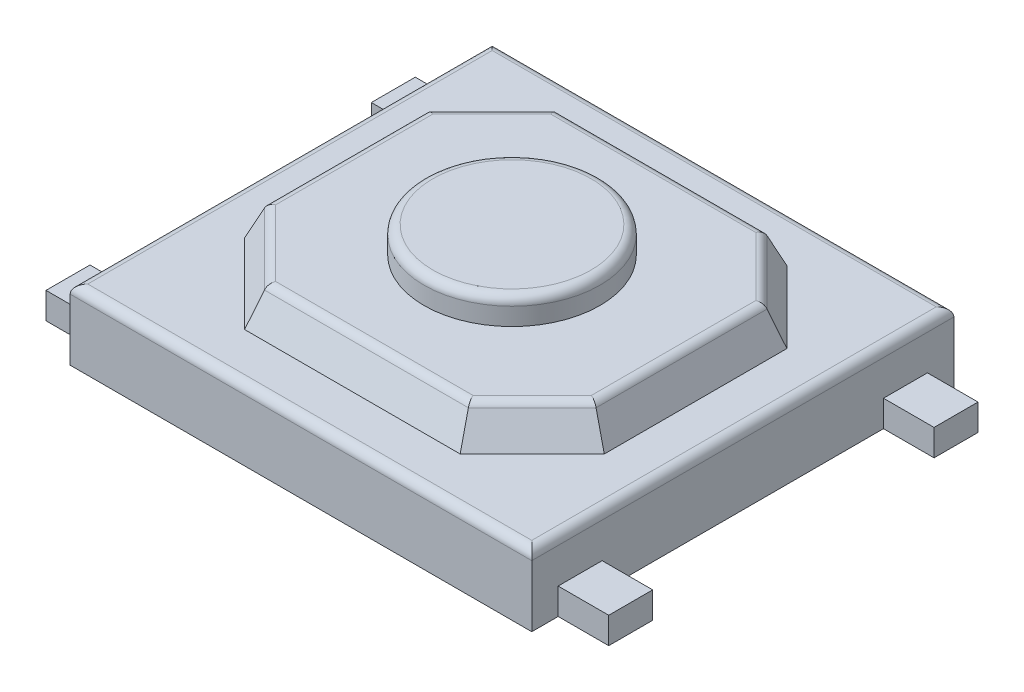
SolidWorks part; units mm, degrees
ref_plane "Front Plane" through (0, 0, 0) normal (0, 0, 1) x (1, 0, 0)
ref_plane "Top Plane" through (0, 0, 0) normal (0, 1, 0) x (1, 0, 0)
ref_plane "Right Plane" through (0, 0, 0) normal (1, 0, 0) x (0, 0, -1)
sketch "Sketch1" plane through (0, 0, 0) normal (0, 1, 0) x (1, 0, 0)
  line L0 (-2.625, -2.4) -> (2.625, -2.4)
  line L1 (-2.625, -2.4) -> (-2.625, 2.4)
  line L2 (2.625, -2.4) -> (2.625, 2.4)
  line L3 (-2.625, 2.4) -> (2.625, 2.4)
  line L4 (-2.625, -2.4) -> (2.625, 2.4) construction
  line L5 (2.625, -2.4) -> (-2.625, 2.4) construction
  point P1 (0, 0)
  dimension "D1" = 5.25
  dimension "D2" = 4.8
extrude "Boss-Extrude1" add sketch "Sketch1" along normal blind 0.8
sketch "Sketch2" plane through (0, 0.8, 0) normal (0, 1, 0) x (1, 0, 0)
  line L0 (-1.1076, -1.67) -> (1.1897, -1.67)
  line L1 (-1.9, -0.8776) -> (-1.9, 0.9629)
  line L2 (1.9, -0.9597) -> (1.9, 0.9629)
  line L3 (-1.1929, 1.67) -> (1.1929, 1.67)
  line L4 (-1.4783, -1.2993) -> (1.5237, 1.3392) construction
  line L5 (1.522, -1.3377) -> (-1.5237, 1.3392) construction
  line L7 (2.625, 2.4) -> (-2.625, 2.4) construction
  line L8 (1.1897, -1.67) -> (1.9, -0.9597)
  line L9 (-1.9, -0.8776) -> (-1.1076, -1.67)
  line L10 (-1.9, 0.9629) -> (-1.1929, 1.67)
  line L11 (1.1929, 1.67) -> (1.9, 0.9629)
  point P1 (0, 0)
  dimension "D1" = 3.8
  dimension "D2" = 0.73
  dimension "D3" = 45
  dimension "D4" = 45
extrude "Boss-Extrude2" add sketch "Sketch2" along normal blind 0.4
sketch "Sketch3" plane through (0, 1.2, 0) normal (0, 1, 0) x (1, 0, 0)
  circle A0 centre (0, 0) radius 1
extrude "Boss-Extrude3" add sketch "Sketch3" along normal blind 0.3
sketch "Sketch4" plane through (2.625, 0, 0) normal (1, 0, 0) x (0, 0, -1)
  line L0 (-2.1, 0) -> (-1.6, 0)
  line L1 (-2.1, 0) -> (-2.1, 0.3)
  line L2 (-1.6, 0) -> (-1.6, 0.3)
  line L3 (-2.1, 0.3) -> (-1.6, 0.3)
  line L4 (-2.4, 0) -> (2.4, 0) construction
  point P6 (0, 0)
  dimension "D1" = 0.5
  dimension "D2" = 1.6
  dimension "D3" = 0.3
extrude "Boss-Extrude4" add sketch "Sketch4" along normal blind 0.575
mirror "Mirror1" about plane through (0, 0, 0) normal (0, 0, 1) of "Boss-Extrude4"
mirror "Mirror2" about plane through (0, 0, 0) normal (1, 0, 0) of "Mirror1", "Boss-Extrude4"
draft "Draft3" type of draft neutral plane draft angle 25 faces to draft 8 face at (1.5449, 1, 1.3149) face at (0.0411, 1, 1.67) face at (-1.5038, 1, 1.2738) face at (-1.9, 1, -0.0427) face at (-1.5464, 1, -1.3164) face at (0, 1, -1.67) face at (1.5464, 1, -1.3164) face at (1.9, 1, -0.0016) neutral plane through (2.8613, 1.2, -0.0016) neutral plane normal (0, 1, 0) parameters "D1"=25
fillet "Fillet1" radius 0.1 12 edges at (1.5464, 1.2, -1.3164) (1.9, 1.2, -0.0016) (1.5449, 1.2, 1.3149) (0.0411, 1.2, 1.67) (-1.5038, 1.2, 1.2738) (-1.9, 1.2, -0.0427) (-1.5464, 1.2, -1.3164) (0, 1.2, -1.67) (0, 0.8, -2.4) (2.625, 0.8, 0) (0, 0.8, 2.4) (-2.625, 0.8, 0)
fillet "Fillet2" radius 0.1 1 edges at (0, 1.5, 1)
